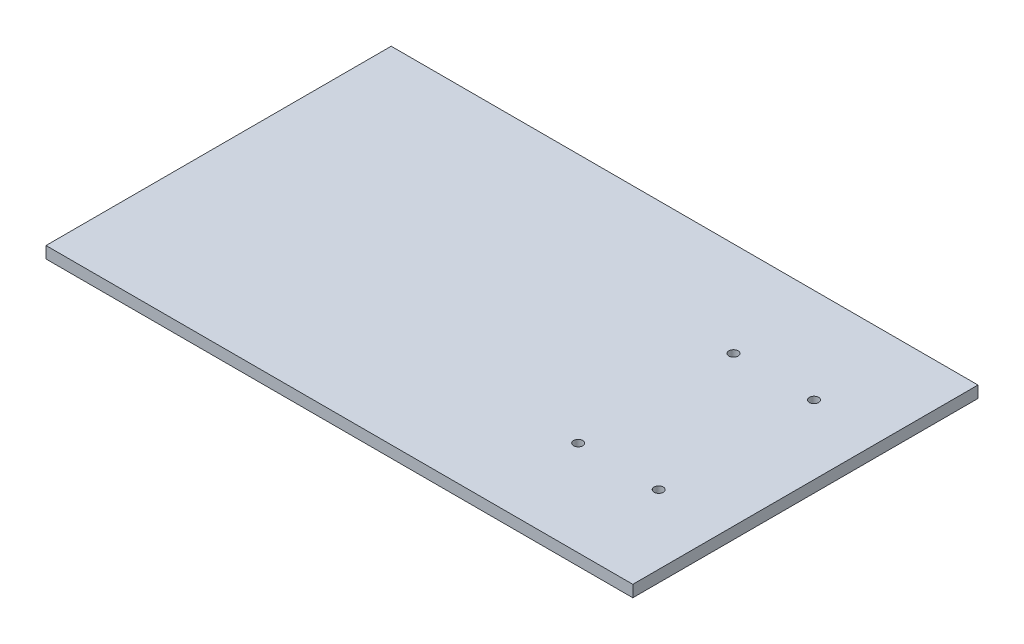
SolidWorks part; units mm, degrees
material "Hexcel AS4C (3000 Filaments)"
ref_plane "Front Plane" through (0, 0, 0) normal (0, 0, 1) x (1, 0, 0)
ref_plane "Top Plane" through (0, 0, 0) normal (0, 1, 0) x (1, 0, 0)
ref_plane "Right Plane" through (0, 0, 0) normal (1, 0, 0) x (0, 0, -1)
sketch "Sketch1" plane through (0, 0, 0) normal (0, 1, 0) x (1, 0, 0)
  line L1 (0, 0) -> (510, 0)
  line L2 (0, 0) -> (0, 300)
  line L3 (0, 300) -> (510, 300)
  line L4 (510, 0) -> (510, 300)
  dimension "D1" = 510
  dimension "D2" = 300
extrude "Boss-Extrude1" add sketch "Sketch1" along normal blind 10.16
sketch "Sketch2" plane through (0, 0, 0) normal (0, -1, 0) x (1, 0, 0)
  line L0 (380, -217.5) -> (380, -82.5) construction
  line L1 (380, -217.5) -> (450, -217.5) construction
  line L2 (450, -217.5) -> (450, -82.5) construction
  line L3 (380, -82.5) -> (450, -82.5) construction
  line L4 (510, -150) -> (450, -150) construction
  line L5 (510, 0) -> (510, -300) construction
  circle A0 centre (380, -217.5) radius 4
  circle A1 centre (380, -82.5) radius 4
  circle A2 centre (450, -82.5) radius 4
  circle A3 centre (450, -217.5) radius 4
  dimension "D1" = 8
  dimension "D2" = 8
  dimension "D3" = 8
  dimension "D4" = 8
  dimension "D5" = 60
extrude "Cut-Extrude1" cut sketch "Sketch2" against normal through all
